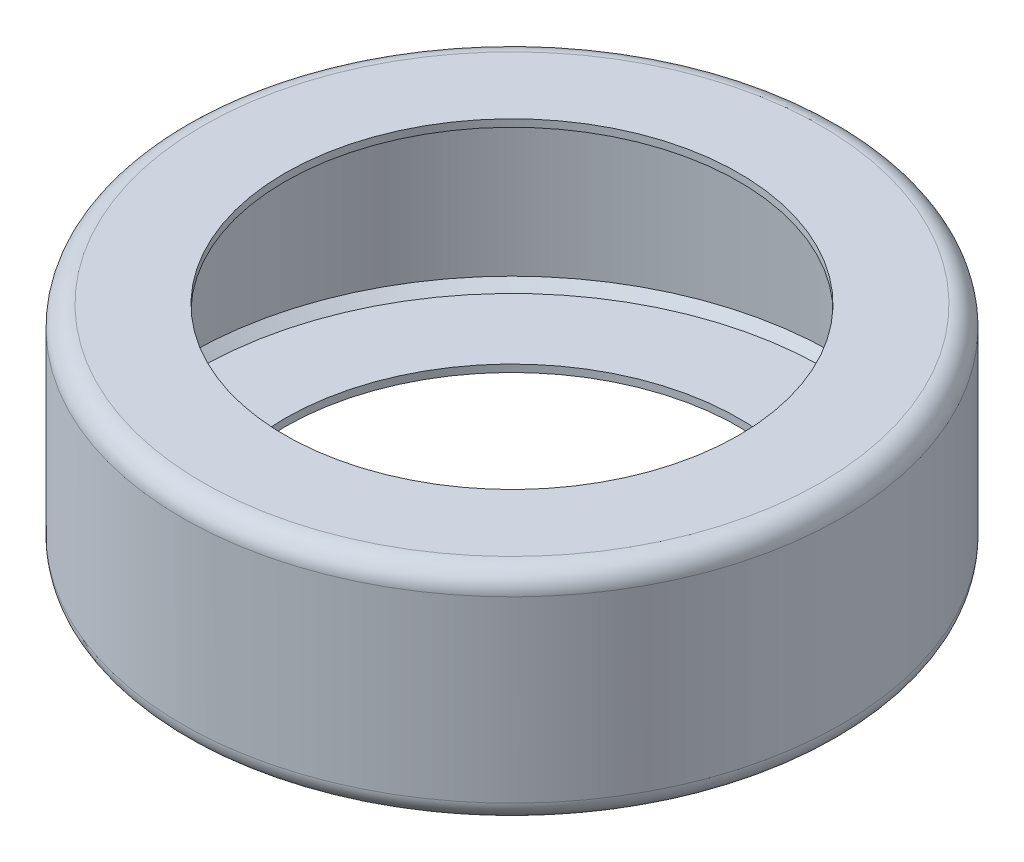
SolidWorks part; units mm, degrees
material "PTFE (general)"
ref_plane "Front Plane" through (0, 0, 0) normal (0, 0, 1) x (1, 0, 0)
ref_plane "Top Plane" through (0, 0, 0) normal (0, 1, 0) x (1, 0, 0)
ref_plane "Right Plane" through (0, 0, 0) normal (1, 0, 0) x (0, 0, -1)
sketch "Sketch1" plane through (0, 0, 0) normal (0, 0, 1) x (1, 0, 0)
  line L0 (0, -3.75) -> (0, 3.75) construction
  line L1 (0, 0) -> (-11, 0) construction
  line L2 (-11.25, 3.75) -> (-11.25, -3.75)
  line L3 (-11.25, -3.75) -> (-7.75, -3.75)
  line L4 (-11.25, 3.75) -> (-7.75, 3.75)
  line L5 (-7.75, 3.75) -> (-7.75, 3.5)
  line L6 (-7.75, 3.5) -> (-11, 3.5)
  line L7 (-11, 3.5) -> (-11, -3.5)
  line L8 (-11, -3.5) -> (-7.75, -3.5)
  line L9 (-7.75, -3.5) -> (-7.75, -3.75)
  line L10 (-11, 0) -> (-11.25, 0) construction
  point P4 (0, 0)
  dimension "D1" = 3.5
  dimension "D2" = 0.25
  dimension "D3" = 11
  dimension "D4" = 7
revolve "Revolve1" add sketch "Sketch1" angle 360 mid plane about L0
fillet "Fillet2" radius 0.7 2 edges at (11.25, 3.75, 0) (11.25, -3.75, 0)
chamfer "Chamfer1" distance 0.3 angle 45 2 edges at (11, -3.5, 0) (11, 3.5, 0)
move or copy body "Body-Move/Copy1" [suppressed] bodies to move or copy 101
